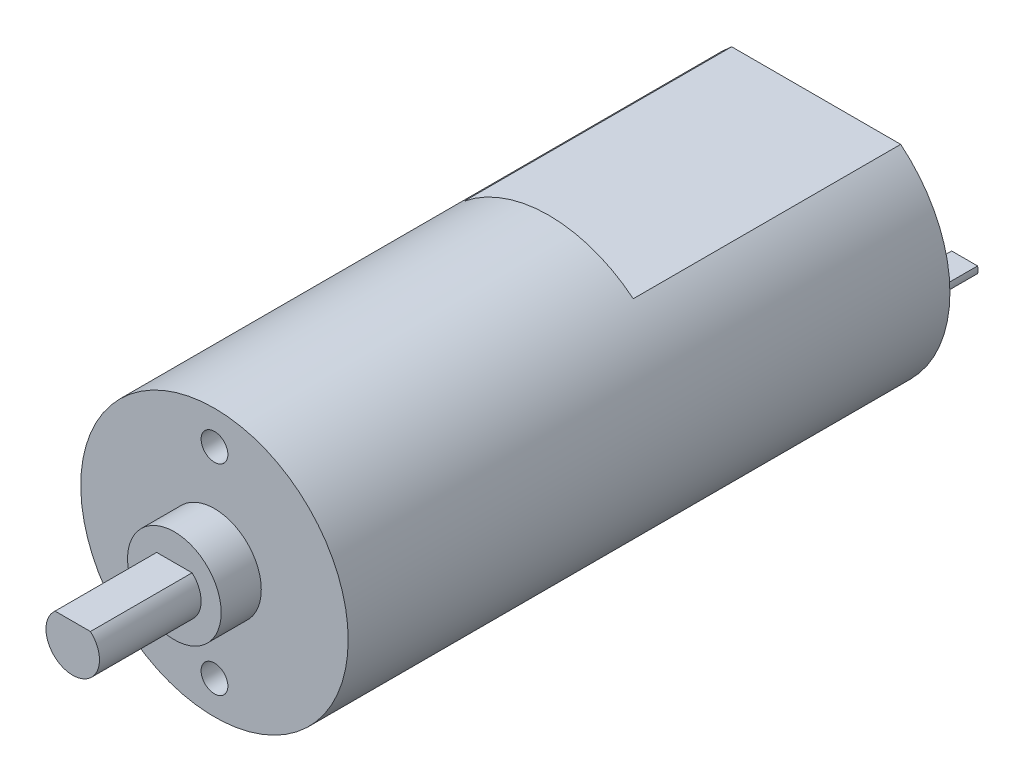
SolidWorks part; units mm, degrees
ref_plane "前视基准面" through (0, 0, 0) normal (0, 0, 1) x (1, 0, 0)
ref_plane "上视基准面" through (0, 0, 0) normal (0, 1, 0) x (1, 0, 0)
ref_plane "右视基准面" through (0, 0, 0) normal (1, 0, 0) x (0, 0, -1)
other "Configuration Table"
sketch "草图1" plane through (0, 0, 0) normal (0, 0, 1) x (1, 0, 0)
  line L0 (-6.3196, 7.75) -> (6.3196, 7.75)
  line L1 (-6.3196, -7.75) -> (6.3196, -7.75)
  arc A0 (6.3196, -7.75) -> (6.3196, 7.75) centre (0, 0) ccw
  arc A1 (-6.3196, 7.75) -> (-6.3196, -7.75) centre (0, 0) ccw
  dimension "D1" = 10
  dimension "D2" = 15.5
extrude "凸台-拉伸1" add sketch "草图1" along normal blind 20
sketch "草图2" plane through (0, 0, 20) normal (0, 0, 1) x (1, 0, 0)
  circle A0 centre (0, 0) radius 10
  dimension "D1" = 20
extrude "凸台-拉伸2" add sketch "草图2" along normal blind 25
sketch "草图3" plane through (0, 0, 45) normal (0, 0, 1) x (1, 0, 0)
  line L0 (0, 0) -> (50000, 0) construction
  line L1 (0, 0) -> (0, -50000) construction
  circle A0 centre (0, 7.5) radius 1
  circle A1 centre (0, -7.5) radius 1
  dimension "D2" = 2
  dimension "D3" = 2
  dimension "D1" = 7.5
  dimension "D4" = 7.5
extrude "切除-拉伸1" cut sketch "草图3" against normal blind 4
sketch "草图4" plane through (0, 0, 0) normal (0, 0, -1) x (-1, 0, 0)
  circle A0 centre (0, 0) radius 3
  dimension "D1" = 6
extrude "凸台-拉伸3" add sketch "草图4" along normal blind 2
sketch "草图5" plane through (0, 0, 0) normal (0, 0, -1) x (-1, 0, 0)
  line L0 (0, 0) -> (0, -50000) construction
  line L1 (7.6, 0.6132) -> (7.6, -49999.3868) construction
  line L2 (-7.6, 0.1304) -> (-7.6, -49999.8696) construction
  line L3 (0, 0) -> (50000, 0) construction
  circle A0 centre (-7.6, -1) radius 1
  circle A1 centre (7.6, 1) radius 1
  dimension "D3" = 2
  dimension "D4" = 2
  dimension "D1" = 15.2
  dimension "D2" = 7.6
extrude "凸台-拉伸4" add sketch "草图5" along normal blind 0.5
sketch "草图6" plane through (0, 0, -0.5) normal (0, 0, -1) x (-1, 0, 0)
  line L1 (-8.5682, -1.25) -> (-6.6318, -1.25)
  line L3 (-8.5682, -0.75) -> (-6.6318, -0.75)
  line L5 (-8.5682, -1.25) -> (-6.6318, -0.75) construction
  line L6 (-8.5682, -0.75) -> (-6.6318, -1.25) construction
  line L7 (6.6318, 0.75) -> (8.5682, 0.75)
  line L9 (6.6318, 1.25) -> (8.5682, 1.25)
  line L11 (6.6318, 0.75) -> (8.5682, 1.25) construction
  line L12 (6.6318, 1.25) -> (8.5682, 0.75) construction
  circle A0 centre (-7.6, -1) radius 1 construction
  circle A1 centre (7.6, 1) radius 1 construction
  arc A2 (-8.5682, -0.75) -> (-8.5682, -1.25) centre (-7.6, -1) ccw
  arc A3 (-6.6318, -0.75) -> (-6.6318, -1.25) centre (-7.6, -1) cw
  arc A4 (8.5682, 1.25) -> (8.5682, 0.75) centre (7.6, 1) cw
  arc A5 (6.6318, 1.25) -> (6.6318, 0.75) centre (7.6, 1) ccw
  point P0 (-7.6, -1)
  point P8 (7.6, 1)
  dimension "D1" = 0.5
  dimension "D4" = 0.5
extrude "凸台-拉伸6" add sketch "草图6" along normal blind 3
sketch "草图7" plane through (0, 0, 45) normal (0, 0, 1) x (1, 0, 0)
  circle A0 centre (0, 0) radius 3.5
  dimension "D1" = 7
extrude "凸台-拉伸7" add sketch "草图7" along normal blind 3
sketch "草图9" plane through (0, 0, 48) normal (0, 0, 1) x (1, 0, 0)
  line L0 (-1.3229, 1.5) -> (1.3229, 1.5)
  line L1 (0, -2) -> (50000, -2) construction
  arc A0 (-1.3229, 1.5) -> (1.3229, 1.5) centre (0, 0) ccw
  point P6 (0, -2)
  dimension "D1" = 4
  dimension "D2" = 3.5
extrude "凸台-拉伸8" add sketch "草图9" along normal blind 7.6
